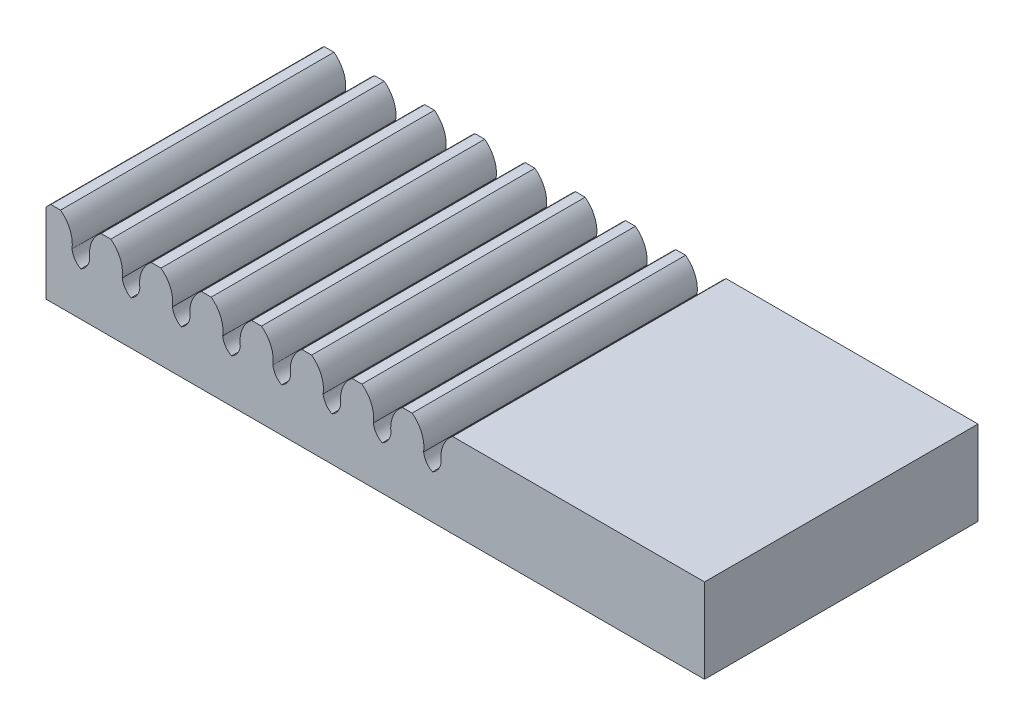
SolidWorks part; units mm, degrees
ref_plane "Front Plane" through (0, 0, 0) normal (0, 0, 1) x (1, 0, 0)
ref_plane "Top Plane" through (0, 0, 0) normal (0, 1, 0) x (1, 0, 0)
ref_plane "Right Plane" through (0, 0, 0) normal (1, 0, 0) x (0, 0, -1)
sketch "Sketch1" plane through (0, 0, 0) normal (0, 0, 1) x (1, 0, 0)
  line L0 (4, 7) -> (-19, 7)
  line L1 (-19, 7) -> (-19, -0.5604)
  line L2 (-19, -0.5604) -> (0.9392, -0.5604)
  line L3 (0.9392, -0.5604) -> (40, -0.5604)
  line L4 (40, -0.5604) -> (40, 7)
  line L5 (40, 7) -> (4, 7)
  dimension "D1" = 7.5604
  dimension "D2" = 23
  dimension "D3" = 36
extrude "Boss-Extrude1" add sketch "Sketch1" along normal blind 24.5
sketch "Sketch2" plane through (0, 0, 0) normal (0, 0, 1) x (1, 0, 0)
  line L0 (-6.8813, 0.8955) -> (-6.8813, 9.6802) construction
  arc A5 (-6.8813, 3.3484) -> (-7.6713, 4.4984) centre (-6.1725, 4.6817) cw
  arc A12 (-7.6713, 4.4984) -> (-8.9813, 7.188) centre (-10.3038, 4.8801) ccw
  arc A13 (-6.0913, 4.4984) -> (-4.7813, 7.188) centre (-3.4588, 4.8801) cw
  arc A14 (-6.8813, 3.3484) -> (-6.0913, 4.4984) centre (-7.5901, 4.6817) ccw
  arc A15 (-8.9813, 7.188) -> (-4.7813, 7.188) centre (-6.8813, 3.6353) cw
  dimension "D4" = 2.66
  dimension "D5" = 1.51
  dimension "D6" = 1.15
  dimension "D8" = 2.1
  dimension "D10" = 0.79
extrude "Cut-Extrude1" cut sketch "Sketch2" along normal blind 26.12
pattern_linear "LPattern1" count 4 spacing 4.5 along (-1, 0, 0) count 6 spacing 4.5 along (1, 0, 0) of "Cut-Extrude1"
